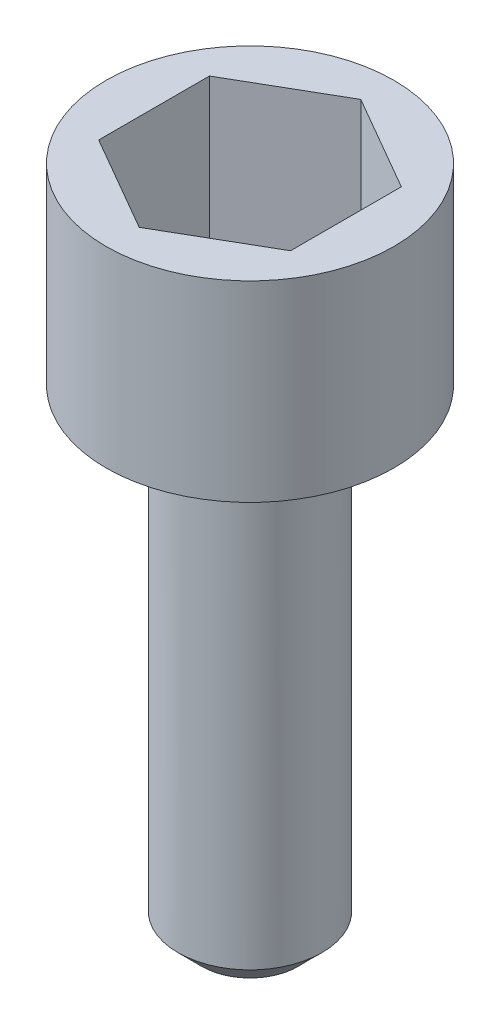
SolidWorks part; units mm, degrees
ref_plane "Front Plane" through (0, 0, 0) normal (0, 0, 1) x (1, 0, 0)
ref_plane "Top Plane" through (0, 0, 0) normal (0, 1, 0) x (1, 0, 0)
ref_plane "Right Plane" through (0, 0, 0) normal (1, 0, 0) x (0, 0, -1)
sketch "Sketch1" plane through (0, 0, 0) normal (0, 0, 1) x (1, 0, 0)
  line L0 (0, 14) -> (-3, 14)
  line L1 (-3, 14) -> (-3, 10)
  line L2 (-3, 10) -> (-1.5, 10)
  line L3 (-1.5, 10) -> (-1.5, 0)
  line L4 (-1.5, 0) -> (0, 0)
  line L5 (0, 0) -> (0, 14)
  point P5 (-1.4842, 15.3186)
  point P7 (0, 0)
  dimension "D1" = 1.5
  dimension "D2" = 10
  dimension "D3" = 4
  dimension "D4" = 3
revolve "Revolve1" add sketch "Sketch1" angle 360 about L5
sketch "Sketch2" plane through (0, 14, 0) normal (0, 1, 0) x (1, 0, 0)
  line L1 (0, 2.3094) -> (-2, 1.1547)
  line L2 (-2, 1.1547) -> (-2, -1.1547)
  line L3 (-2, -1.1547) -> (0, -2.3094)
  line L4 (0, -2.3094) -> (2, -1.1547)
  line L5 (2, -1.1547) -> (2, 1.1547)
  line L6 (2, 1.1547) -> (0, 2.3094)
  circle A0 centre (0, 0) radius 2 construction
  point P1 (0, 0)
  dimension "D1" = 4
extrude "Cut-Extrude1" cut sketch "Sketch2" against normal blind 3
chamfer "Chamfer1" distance 0.5 angle 45 1 edges at (0, 0, -1.5)
